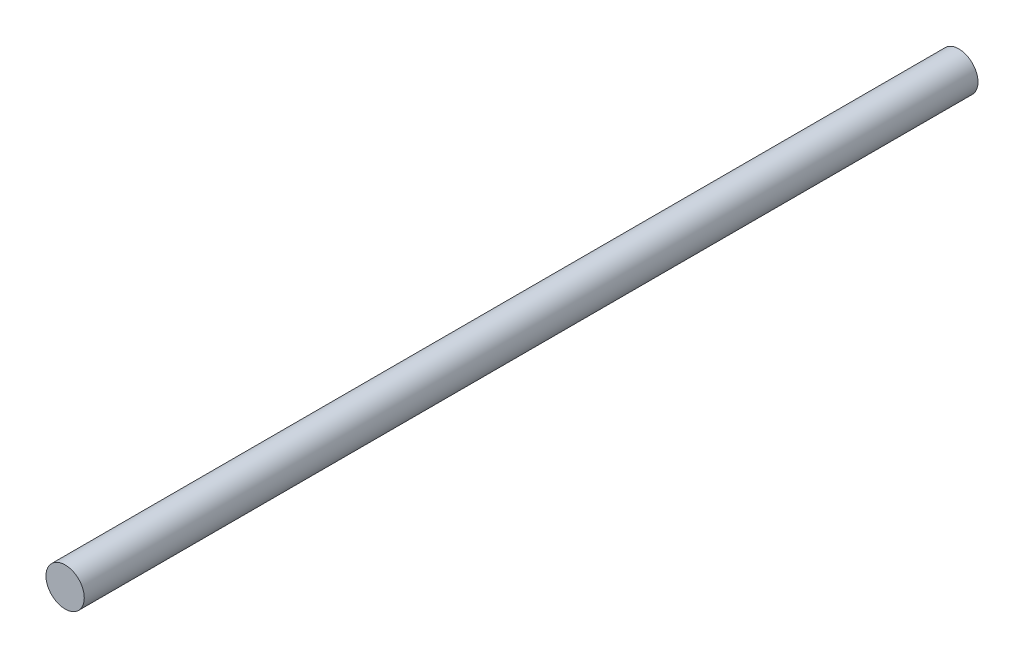
SolidWorks part; units mm, degrees
ref_plane "Front Plane" through (0, 0, 0) normal (0, 0, 1) x (1, 0, 0)
ref_plane "Top Plane" through (0, 0, 0) normal (0, 1, 0) x (1, 0, 0)
ref_plane "Right Plane" through (0, 0, 0) normal (1, 0, 0) x (0, 0, -1)
sketch "Sketch1" plane through (0, 0, 0) normal (0, 0, 1) x (1, 0, 0)
  circle A0 centre (0, 0) radius 7.5
extrude "Boss-Extrude1" add sketch "Sketch1" along normal blind 350
